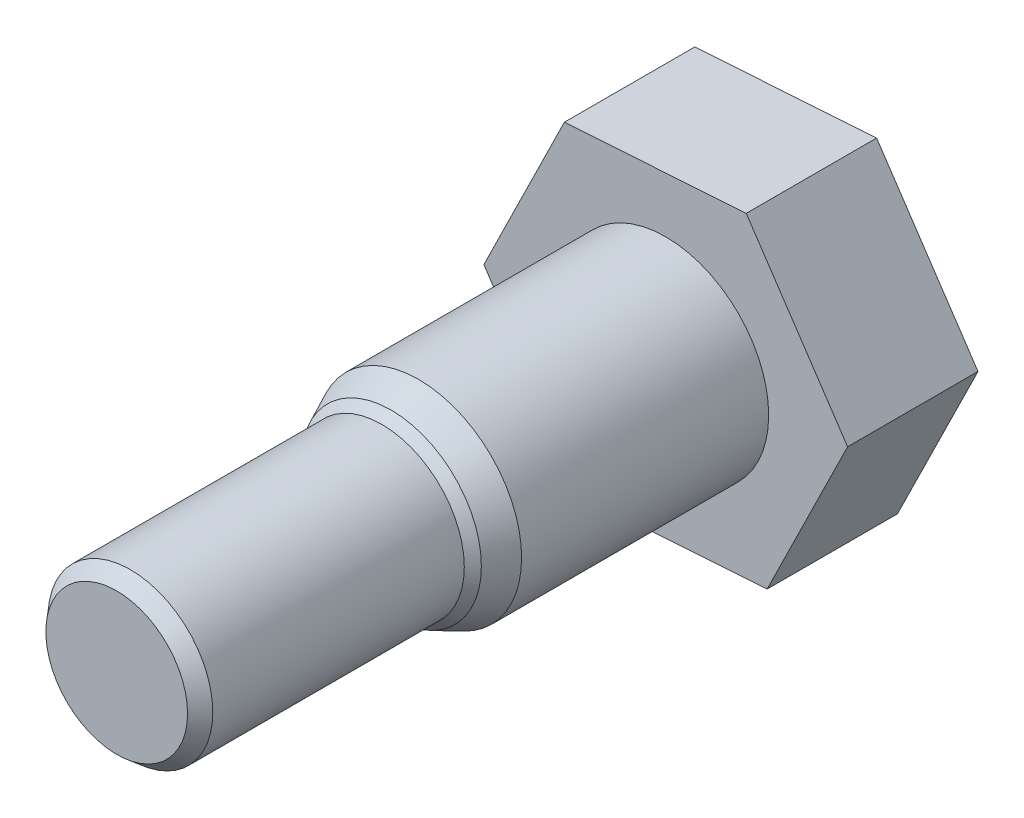
SolidWorks part; units mm, degrees
ref_plane "前视基准面" through (0, 0, 0) normal (0, 0, 1) x (1, 0, 0)
ref_plane "上视基准面" through (0, 0, 0) normal (0, 1, 0) x (1, 0, 0)
ref_plane "右视基准面" through (0, 0, 0) normal (1, 0, 0) x (0, 0, -1)
sketch "草图1" plane through (0, 0, 0) normal (0, 0, 1) x (1, 0, 0)
  circle A0 centre (0, 0) radius 15
  dimension "D1" = 30
extrude "拉伸1" add sketch "草图1" along normal blind 1
sketch "草图2" plane through (0, 0, 0) normal (0, 0, 1) x (1, 0, 0)
  line L1 (14.7707, -22.0717) -> (26.5, 1.7559)
  line L2 (26.5, 1.7559) -> (11.7293, 23.8276)
  line L3 (11.7293, 23.8276) -> (-14.7707, 22.0717)
  line L4 (-14.7707, 22.0717) -> (-26.5, -1.7559)
  line L5 (-26.5, -1.7559) -> (-11.7293, -23.8276)
  line L6 (-11.7293, -23.8276) -> (14.7707, -22.0717)
  circle A0 centre (0, 0) radius 23 construction
  dimension "D1" = 46
  dimension "D2" = 53
extrude "拉伸2" add sketch "草图2" along normal blind 19
sketch "草图9" plane through (0, 0, 19) normal (0, 0, 1) x (1, 0, 0)
  circle A0 centre (0, 0) radius 15
  dimension "D1" = 30
extrude "拉伸3" add sketch "草图9" along normal blind 36
sketch "草图11" plane through (0, 0, 55) normal (0, 0, 1) x (1, 0, 0)
  circle A0 centre (0, 0) radius 15
  dimension "D1" = 30
extrude "拉伸6" add sketch "草图11" along normal blind 4 draft 25
sketch "草图12" plane through (0, 0, 59) normal (0, 0, 1) x (1, 0, 0)
  circle A0 centre (0, 0) radius 12
  dimension "D1" = 24
extrude "拉伸7" add sketch "草图12" along normal blind 38
sketch "草图13" plane through (0, 0, 59) normal (0, 0, 1) x (1, 0, 0)
  circle A0 centre (0, 0) radius 13.1348
  dimension "D1" = 26.2695
extrude "拉伸8" add sketch "草图13" along normal blind 2 draft 40
sketch "草图15" plane through (0, 0, 97) normal (0, 0, 1) x (1, 0, 0)
  circle A0 centre (0, 0) radius 12
  dimension "D1" = 24
extrude "拉伸9" add sketch "草图15" along normal blind 2 draft 40
